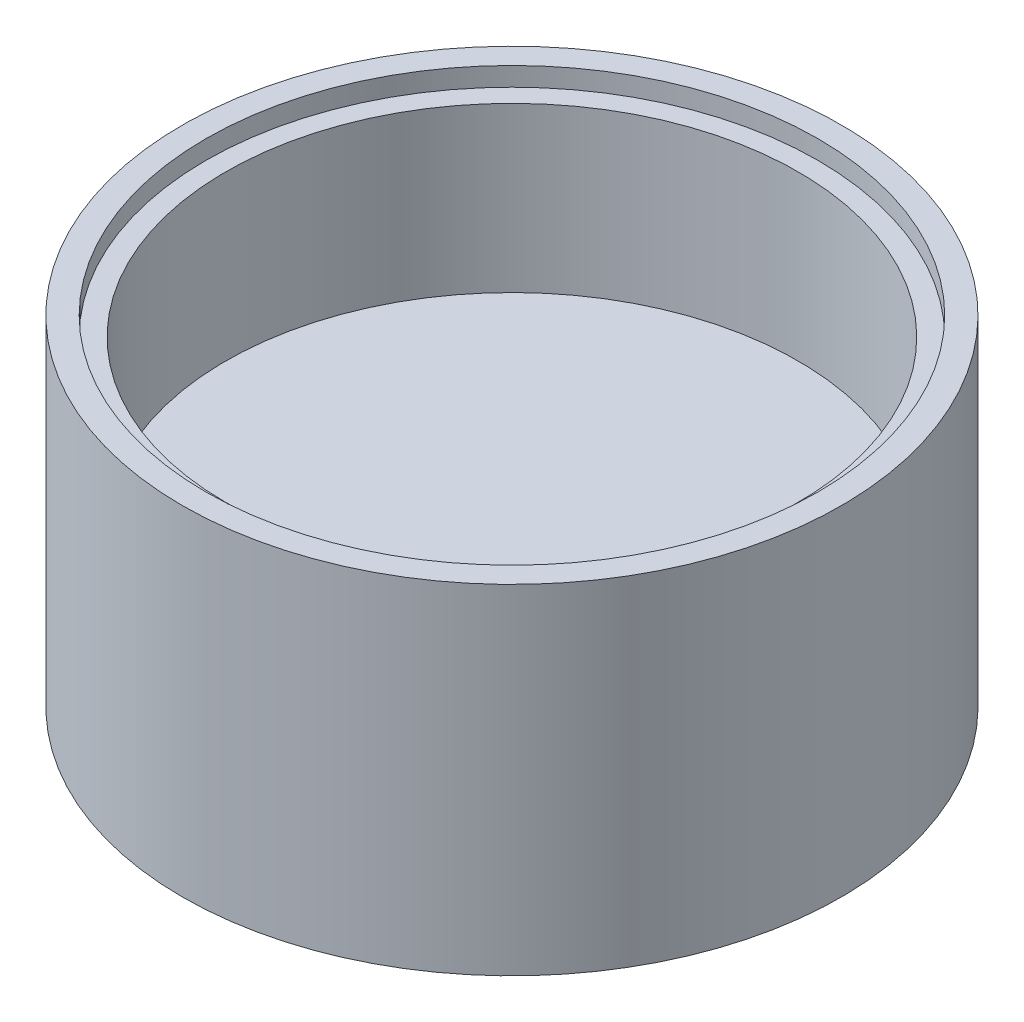
SolidWorks part; units mm, degrees
ref_plane "Front Plane" through (0, 0, 0) normal (0, 0, 1) x (1, 0, 0)
ref_plane "Top Plane" through (0, 0, 0) normal (0, 1, 0) x (1, 0, 0)
ref_plane "Right Plane" through (0, 0, 0) normal (1, 0, 0) x (0, 0, -1)
sketch "Sketch1" plane through (0, 0, 0) normal (0, 1, 0) x (1, 0, 0)
  circle A0 centre (0, 0) radius 17.5
  dimension "D1" = 35
extrude "Boss-Extrude1" add sketch "Sketch1" along normal blind 18
shell "Shell1" thickness 2.3
sketch "Sketch2" plane through (0, 18, 0) normal (0, 1, 0) x (1, 0, 0)
  circle A0 centre (0, 0) radius 16.25
  dimension "D1" = 32.5
extrude "Cut-Extrude1" cut sketch "Sketch2" against normal blind 1
sketch "Sketch4" plane through (0, 2.3, 0) normal (0, 1, 0) x (1, 0, 0)
  circle A0 centre (0, 0) radius 15.2
extrude "Boss-Extrude2" add sketch "Sketch4" along normal blind 6
